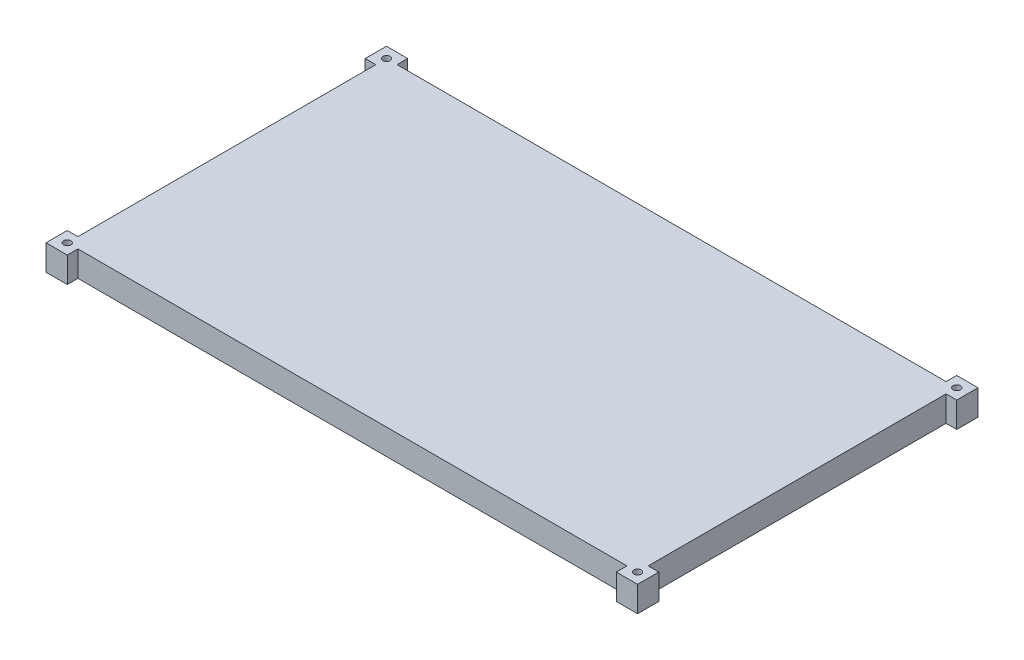
SolidWorks part; units mm, degrees
ref_plane "Front Plane" through (0, 0, 0) normal (0, 0, 1) x (1, 0, 0)
ref_plane "Top Plane" through (0, 0, 0) normal (0, 1, 0) x (1, 0, 0)
ref_plane "Right Plane" through (0, 0, 0) normal (1, 0, 0) x (0, 0, -1)
sketch "Sketch3" plane through (0, 0, 0) normal (0, 1, 0) x (1, 0, 0)
  line L1 (-85.09, -47.625) -> (85.09, -47.625)
  line L2 (-85.09, -47.625) -> (-85.09, 47.625)
  line L3 (-85.09, 47.625) -> (85.09, 47.625)
  line L4 (85.09, -47.625) -> (85.09, 47.625)
  line L5 (-85.09, -47.625) -> (85.09, 47.625) construction
  line L6 (-85.09, 47.625) -> (85.09, -47.625) construction
  point P0 (0, 0)
  dimension "D1" = 95.25
  dimension "D2" = 170.18
extrude "Boss-Extrude1" add sketch "Sketch3" along normal blind 7.62
sketch "Sketch4" plane through (0, 7.62, 0) normal (0, 1, 0) x (1, 0, 0)
  line L1 (-88.265, 44.45) -> (-81.915, 44.45)
  line L2 (-88.265, 44.45) -> (-88.265, 50.8)
  line L3 (-88.265, 50.8) -> (-81.915, 50.8)
  line L4 (-81.915, 44.45) -> (-81.915, 50.8)
  line L5 (-88.265, 44.45) -> (-81.915, 50.8) construction
  line L6 (-88.265, 50.8) -> (-81.915, 44.45) construction
  line L7 (-88.265, -50.8) -> (-81.915, -50.8)
  line L8 (-88.265, -50.8) -> (-88.265, -44.45)
  line L9 (-88.265, -44.45) -> (-81.915, -44.45)
  line L10 (-81.915, -50.8) -> (-81.915, -44.45)
  line L11 (-88.265, -50.8) -> (-81.915, -44.45) construction
  line L12 (-88.265, -44.45) -> (-81.915, -50.8) construction
  line L13 (81.915, 44.45) -> (88.265, 44.45)
  line L14 (81.915, 44.45) -> (81.915, 50.8)
  line L15 (81.915, 50.8) -> (88.265, 50.8)
  line L16 (88.265, 44.45) -> (88.265, 50.8)
  line L17 (81.915, 44.45) -> (88.265, 50.8) construction
  line L18 (81.915, 50.8) -> (88.265, 44.45) construction
  line L19 (81.915, -50.8) -> (88.265, -50.8)
  line L20 (81.915, -50.8) -> (81.915, -44.45)
  line L21 (81.915, -44.45) -> (88.265, -44.45)
  line L22 (88.265, -50.8) -> (88.265, -44.45)
  line L23 (81.915, -50.8) -> (88.265, -44.45) construction
  line L24 (81.915, -44.45) -> (88.265, -50.8) construction
  point P0 (-85.09, 47.625)
  point P6 (-85.09, -47.625)
  point P12 (85.09, 47.625)
  point P18 (85.09, -47.625)
  dimension "D1" = 6.35
extrude "Boss-Extrude3" add sketch "Sketch4" against normal blind 7.62
sketch "Sketch6" plane through (0, 7.62, 0) normal (0, 1, 0) x (1, 0, 0)
  line L0 (-81.915, 50.8) -> (-88.265, 50.8) construction
  line L1 (-88.265, 50.8) -> (-88.265, 44.45) construction
  line L2 (-85.09, -44.45) -> (-88.265, -44.45) construction
  line L3 (-81.915, -50.8) -> (-81.915, -47.625) construction
  line L4 (88.265, -44.45) -> (85.09, -44.45) construction
  line L5 (88.265, -50.8) -> (88.265, -44.45) construction
  line L6 (88.265, 50.8) -> (81.915, 50.8) construction
  line L7 (88.265, 44.45) -> (88.265, 50.8) construction
  circle A0 centre (-85.09, 47.625) radius 1.0922
  circle A1 centre (-85.09, -47.625) radius 1.0922
  circle A2 centre (85.09, -47.625) radius 1.0922
  circle A3 centre (85.09, 47.625) radius 1.0922
  dimension "D1" = 2.1844
  dimension "D4" = 3.175
  dimension "D5" = 3.175
  dimension "D6" = 3.175
  dimension "D7" = 3.175
  dimension "D9" = 3.175
  dimension "D2" = 3.175
  dimension "D3" = 3.175
  dimension "D8" = 3.175
extrude "Cut-Extrude1" cut sketch "Sketch6" against normal blind 10.16
